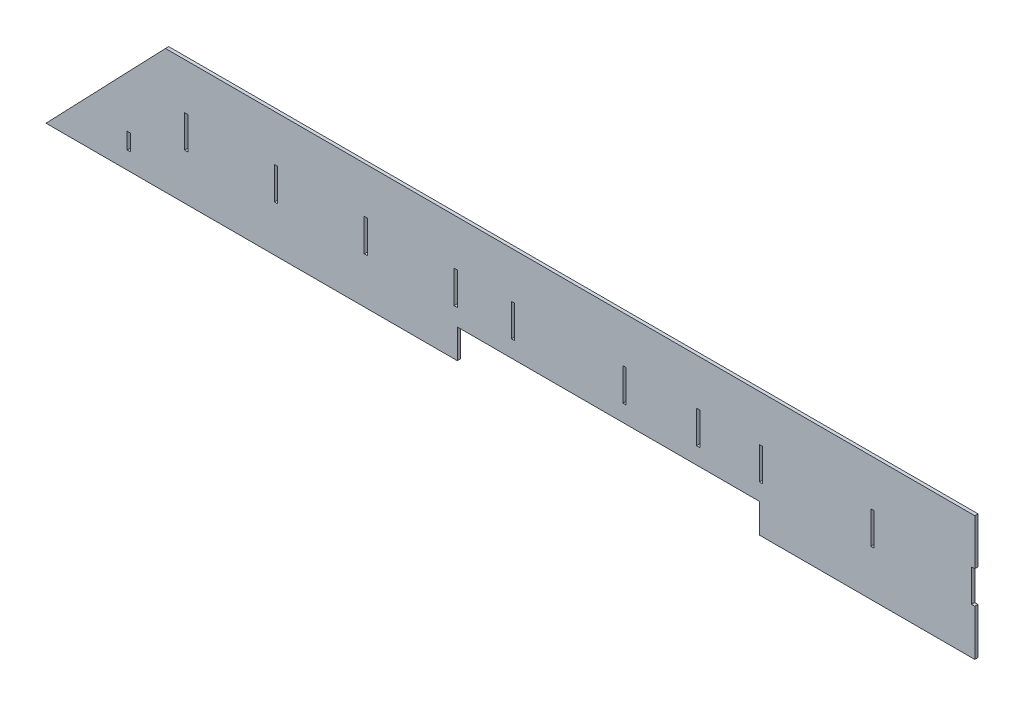
SolidWorks part; units mm, degrees
ref_plane "Front Plane" through (0, 0, 0) normal (0, 0, 1) x (1, 0, 0)
ref_plane "Top Plane" through (0, 0, 0) normal (0, 1, 0) x (1, 0, 0)
ref_plane "Right Plane" through (0, 0, 0) normal (1, 0, 0) x (0, 0, -1)
sketch "Sketch1" plane through (0, 0, 0) normal (0, 0, 1) x (1, 0, 0)
  line L0 (0, 0) -> (110.3511, 115)
  line L1 (110.3511, 115) -> (858, 115)
  line L3 (858, 0) -> (0, 0)
  line L4 (1244.614, 57.5) -> (-683.0281, 57.5) construction
  line L5 (128, 72.5) -> (131, 72.5)
  line L6 (128, 72.5) -> (128, 42.5)
  line L7 (128, 42.5) -> (131, 42.5)
  line L8 (131, 72.5) -> (131, 42.5)
  line L9 (75, 31.1091) -> (78, 31.1091)
  line L10 (75, 31.1091) -> (75, 16.1091)
  line L11 (75, 16.1091) -> (78, 16.1091)
  line L12 (78, 31.1091) -> (78, 16.1091)
  line L14 (211, 72.5) -> (214, 72.5)
  line L15 (211, 72.5) -> (211, 42.5)
  line L16 (211, 42.5) -> (214, 42.5)
  line L17 (214, 72.5) -> (214, 42.5)
  line L18 (294, 72.5) -> (297, 72.5)
  line L19 (294, 72.5) -> (294, 42.5)
  line L20 (294, 42.5) -> (297, 42.5)
  line L21 (297, 72.5) -> (297, 42.5)
  line L22 (377, 72.5) -> (380, 72.5)
  line L23 (377, 72.5) -> (377, 42.5)
  line L24 (377, 42.5) -> (380, 42.5)
  line L25 (380, 72.5) -> (380, 42.5)
  line L26 (430, 72.5) -> (433, 72.5)
  line L27 (430, 72.5) -> (430, 42.5)
  line L28 (430, 42.5) -> (433, 42.5)
  line L29 (433, 72.5) -> (433, 42.5)
  line L30 (533, 72.5) -> (536, 72.5)
  line L31 (533, 72.5) -> (533, 42.5)
  line L32 (533, 42.5) -> (536, 42.5)
  line L33 (536, 72.5) -> (536, 42.5)
  line L34 (601, 72.5) -> (604, 72.5)
  line L35 (601, 72.5) -> (601, 42.5)
  line L36 (601, 42.5) -> (604, 42.5)
  line L37 (604, 72.5) -> (604, 42.5)
  line L38 (659, 72.5) -> (662, 72.5)
  line L39 (659, 72.5) -> (659, 42.5)
  line L40 (659, 42.5) -> (662, 42.5)
  line L41 (662, 72.5) -> (662, 42.5)
  line L42 (762, 72.5) -> (765, 72.5)
  line L43 (762, 72.5) -> (762, 42.5)
  line L44 (762, 42.5) -> (765, 42.5)
  line L45 (765, 72.5) -> (765, 42.5)
  line L46 (855, 72.5) -> (858, 72.5)
  line L47 (855, 72.5) -> (855, 42.5)
  line L48 (855, 42.5) -> (858, 42.5)
  line L53 (858, 72.5) -> (858, 115)
  line L54 (858, 42.5) -> (858, 0)
  dimension "D1" = 115
  dimension "D2" = 30
  dimension "D3" = 3
  dimension "D4" = 15
  dimension "D5" = 3
  dimension "D6" = 75
  dimension "D7" = 50
  dimension "D8" = 30
  dimension "D9" = 3
  dimension "D10" = 30
  dimension "D11" = 3
  dimension "D12" = 80
  dimension "D13" = 80
  dimension "D14" = 80
  dimension "D15" = 3
  dimension "D16" = 30
  dimension "D17" = 50
  dimension "D18" = 3
  dimension "D19" = 30
  dimension "D20" = 100
  dimension "D21" = 3
  dimension "D22" = 30
  dimension "D23" = 65
  dimension "D24" = 30
  dimension "D25" = 3
  dimension "D26" = 55
  dimension "D27" = 3
  dimension "D28" = 30
  dimension "D29" = 3
  dimension "D30" = 30
  dimension "D31" = 100
  dimension "D32" = 90
  dimension "D33" = 3
  dimension "D34" = 30
extrude "Boss-Extrude1" add sketch "Sketch1" along normal blind 3 contours L3 L0 L1
sketch "Sketch2" plane through (0, 0, 3) normal (0, 0, 1) x (1, 0, 0)
  line L0 (0, 0) -> (858, 0) construction
  line L1 (380, 0) -> (659, 0)
  line L2 (380, 0) -> (380, 27)
  line L3 (380, 27) -> (659, 27)
  line L4 (659, 0) -> (659, 27)
  line L6 (380, 42.5) -> (380, 72.5) construction
  line L7 (659, 72.5) -> (659, 42.5) construction
  point P10 (0, 0)
  dimension "D1" = 27
extrude "Cut-Extrude1" cut sketch "Sketch2" against normal blind 10
